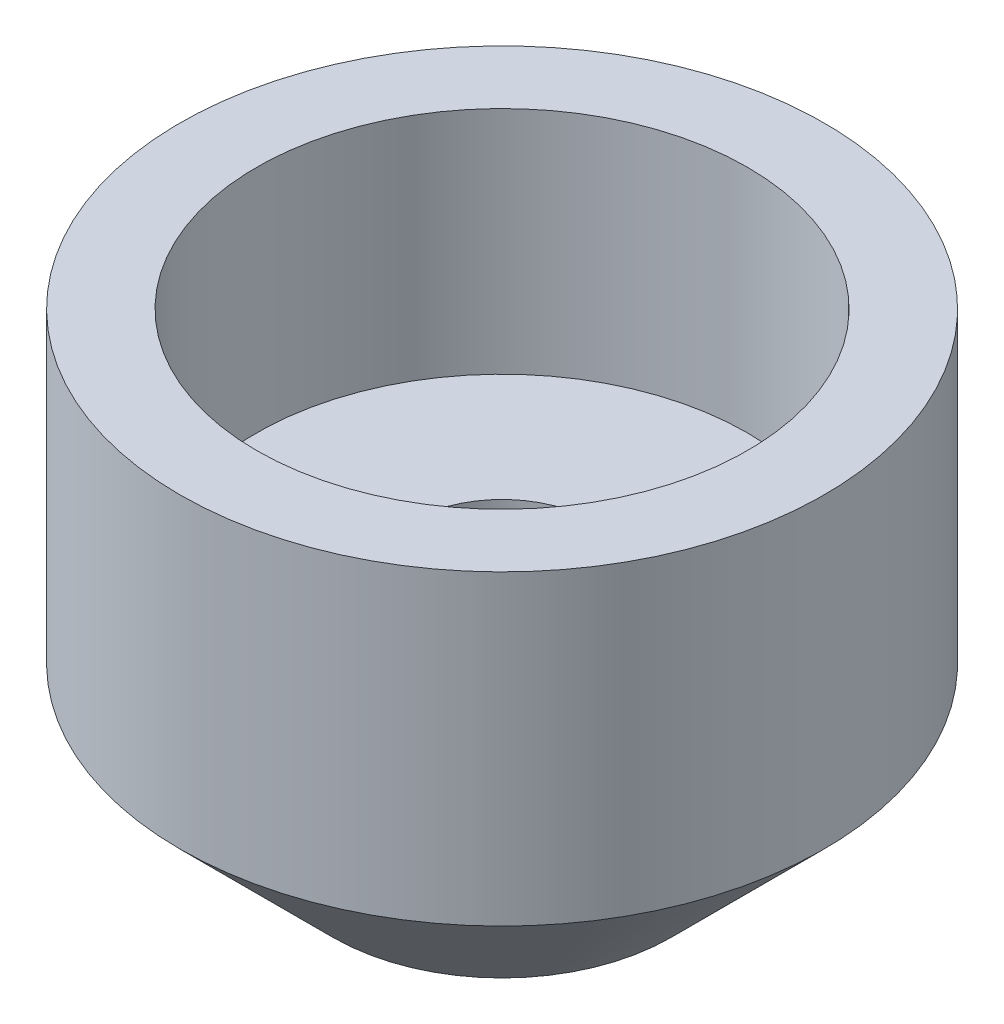
SolidWorks part; units mm, degrees
material "Brass"
ref_plane "Front Plane" through (0, 0, 0) normal (0, 0, 1) x (1, 0, 0)
ref_plane "Top Plane" through (0, 0, 0) normal (0, 1, 0) x (1, 0, 0)
ref_plane "Right Plane" through (0, 0, 0) normal (1, 0, 0) x (0, 0, -1)
sketch "Sketch1" plane through (0, 0, 0) normal (0, 1, 0) x (1, 0, 0)
  circle A0 centre (0, 0) radius 10.5
  dimension "D1" = 21
extrude "Boss-Extrude1" add sketch "Sketch1" along normal blind 15
sketch "Sketch2" plane through (0, 15, 0) normal (0, 1, 0) x (1, 0, 0)
  circle A0 centre (0, 0) radius 8
  dimension "D1" = 16
extrude "Cut-Extrude1" cut sketch "Sketch2" against normal blind 7.5
sketch "Sketch3" plane through (0, 0, 0) normal (0, -1, 0) x (1, 0, 0)
  circle A0 centre (0, 0) radius 3
  dimension "D1" = 6
extrude "Cut-Extrude2" cut sketch "Sketch3" against normal blind 7.5
chamfer "Chamfer1" distance 5 angle 45 1 edges at (0, 0, 10.5)
